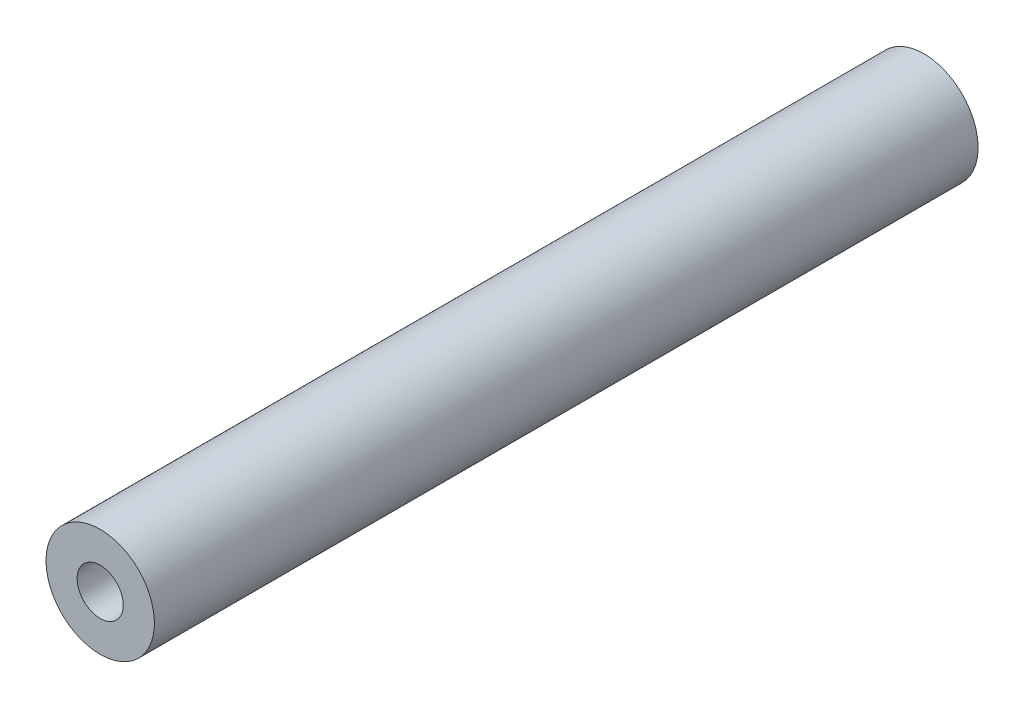
SolidWorks part; units mm, degrees
ref_plane "Front Plane" through (0, 0, 0) normal (0, 0, 1) x (1, 0, 0)
ref_plane "Top Plane" through (0, 0, 0) normal (0, 1, 0) x (1, 0, 0)
ref_plane "Right Plane" through (0, 0, 0) normal (1, 0, 0) x (0, 0, -1)
sketch "Sketch1" plane through (0, 0, 0) normal (0, 0, 1) x (1, 0, 0)
  circle A0 centre (0, 0) radius 3.175
  dimension "D1" = 6.35
extrude "Boss-Extrude1" add sketch "Sketch1" along normal blind 48.26
sketch "Sketch2" plane through (0, 0, 48.26) normal (0, 0, 1) x (1, 0, 0)
  circle A0 centre (0, 0) radius 1.778
  dimension "D1" = 3.556
hole_wizard "#6-32 Tapped Hole1" positions "Sketch3" profile "Sketch4" tap size "#6-32" standard "ANSI Inch"
sketch "Sketch3" plane through (0, 0, 48.26) normal (0, 0, 1) x (1, 0, 0)
  point P0 (0, 0)
sketch "Sketch4" plane through (0, 0, 48.26) normal (1, 0, 0) x (0, -1, 0)
  line L0 (0, 0) -> (0, 13.5127)
  line L1 (0, 13.5127) -> (1.3525, 12.7)
  line L2 (1.3525, 12.7) -> (1.3525, 0)
  line L5 (1.3525, 0) -> (0, 0)
  line L10 (0, 13.5127) -> (-1.3525, 12.7) construction
  line L11 (0, -6.35) -> (0, 107.95) construction
  dimension "Tap Drill Dia." = 2.7051
  dimension "Tap Drill Depth" = 12.7
  dimension "Drill Angle" = 118
cosmetic thread "Hole Thread1" parameters "D1"=7.112, "D2"=3.5052
ref_plane "Plane1" through (0, 0, 24.13) normal (0, 0, 1) x (1, 0, 0)
mirror "Mirror1" about plane through (0, 0, 24.13) normal (0, 0, 1) of "#6-32 Tapped Hole1"
cosmetic thread "Hole Thread2" parameters "D1"=7.112, "D2"=3.5052
